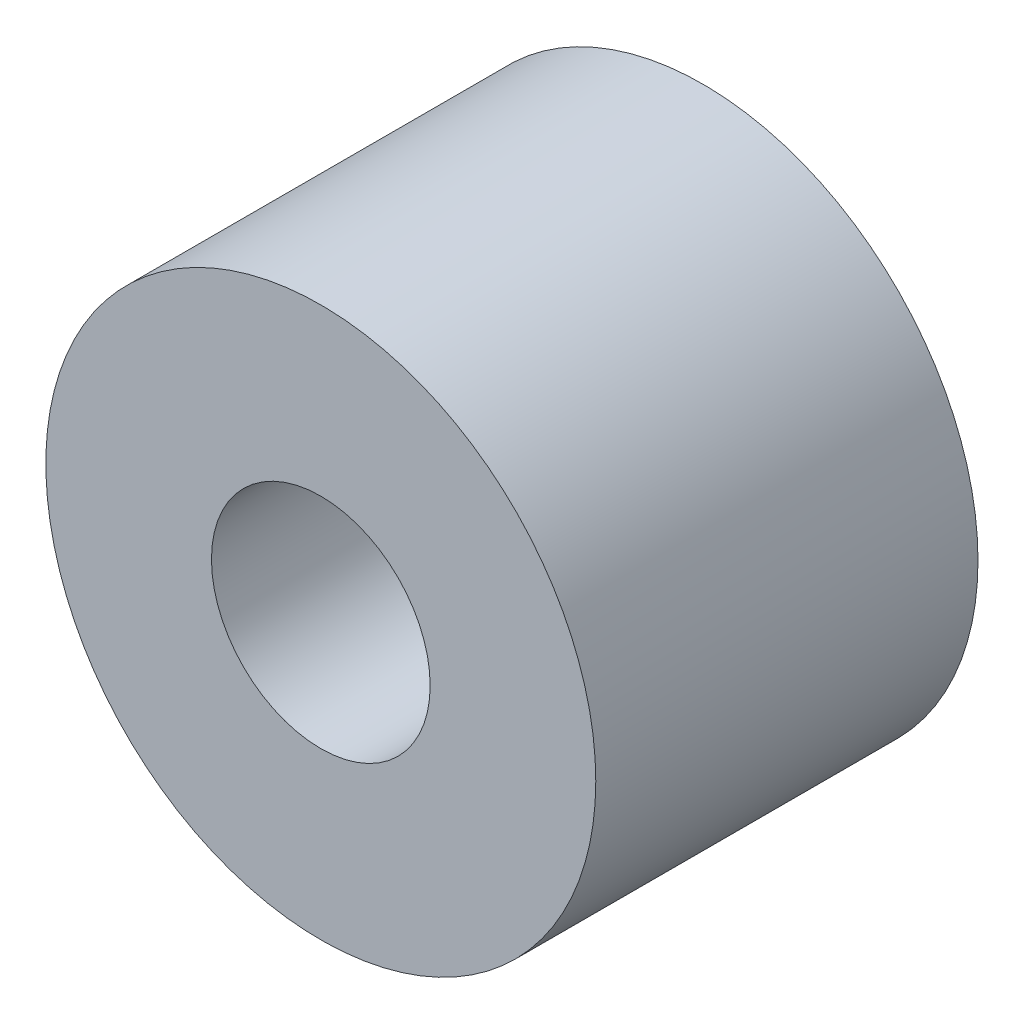
SolidWorks part; units mm, degrees
ref_plane "Front Plane" through (0, 0, 0) normal (0, 0, 1) x (1, 0, 0)
ref_plane "Top Plane" through (0, 0, 0) normal (0, 1, 0) x (1, 0, 0)
ref_plane "Right Plane" through (0, 0, 0) normal (1, 0, 0) x (0, 0, -1)
sketch "Sketch1" plane through (0, 0, 0) normal (0, 0, 1) x (1, 0, 0)
  circle A0 centre (0, 0) radius 12.95
  circle A1 centre (0, 0) radius 5.15
  dimension "D1" = 25.9
  dimension "D2" = 10.3
extrude "Boss-Extrude1" add sketch "Sketch1" along normal blind 18
